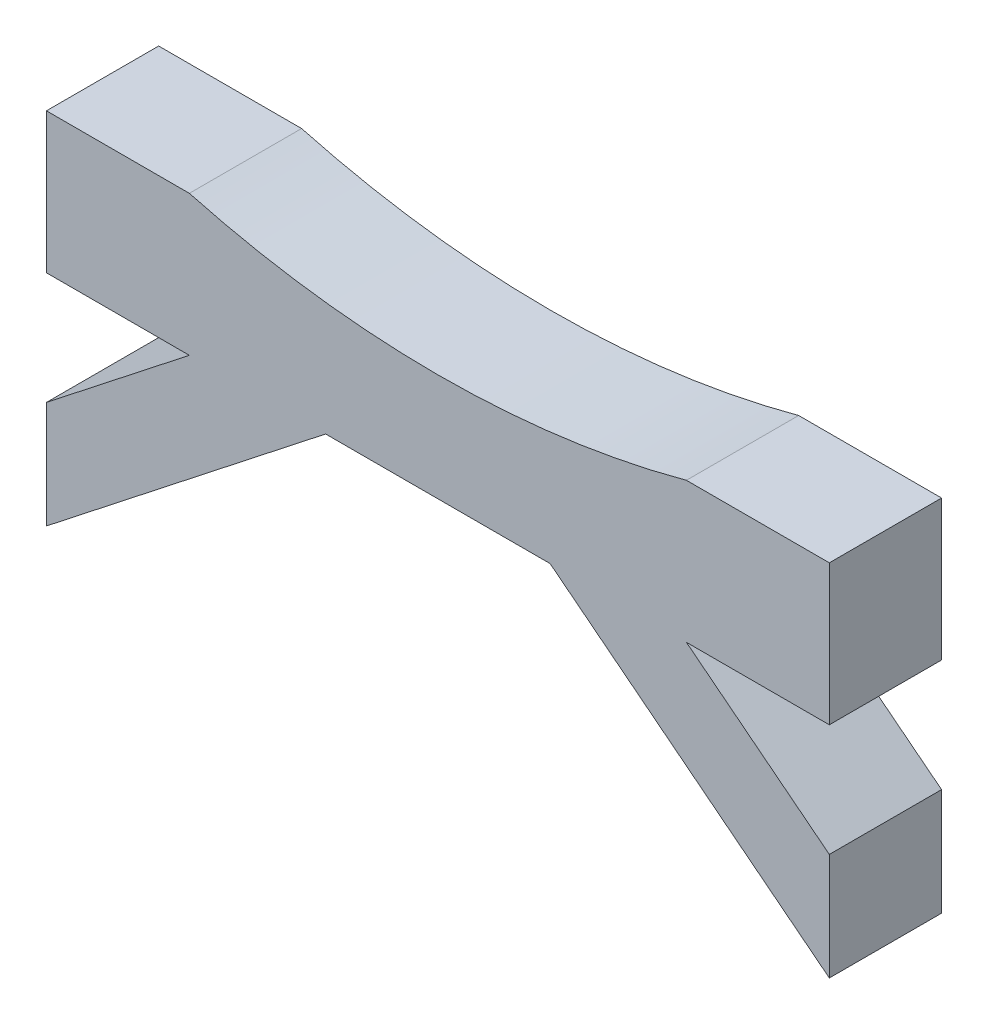
SolidWorks part; units mm, degrees
ref_plane "Front Plane" through (0, 0, 0) normal (0, 0, 1) x (1, 0, 0)
ref_plane "Top Plane" through (0, 0, 0) normal (0, 1, 0) x (1, 0, 0)
ref_plane "Right Plane" through (0, 0, 0) normal (1, 0, 0) x (0, 0, -1)
sketch "Sketch1" plane through (0, 0, 0) normal (0, 0, 1) x (1, 0, 0)
  line L0 (6.4687, 0) -> (0, -5.08)
  line L1 (0, 0) -> (6.4687, 0)
  line L2 (0, 0) -> (0, 6.35)
  line L3 (0, 6.35) -> (6.4687, 6.35)
  line L4 (17.7174, 0) -> (17.7174, 4.8591) construction
  line L5 (0, -5.08) -> (0, -9.9244)
  line L6 (0, -9.9244) -> (12.6374, 0)
  line L7 (17.7174, 4.8591) -> (17.7174, -5.9378) construction
  line L8 (12.6374, 0) -> (22.7974, 0)
  line L9 (35.4348, 0) -> (35.4348, 6.35)
  line L10 (35.4348, -9.9244) -> (22.7974, 0)
  line L11 (35.4348, -5.08) -> (35.4348, -9.9244)
  line L12 (28.9661, 0) -> (35.4348, -5.08)
  line L13 (35.4348, 0) -> (28.9661, 0)
  line L14 (28.9661, 6.35) -> (35.4348, 6.35)
  arc A0 (6.4687, 6.35) -> (28.9661, 6.35) centre (17.7174, 48.0391) ccw
  point P18 (29.4723, 5.08)
  point P19 (24.13, 0)
  dimension "D6" = 43.18
  dimension "D1" = 17.78
  dimension "D2" = 6.35
  dimension "D3" = 3.81
  dimension "D4" = 5.08
  dimension "D5" = 5.08
extrude "Boss-Extrude1" add sketch "Sketch1" along normal blind 5.08
